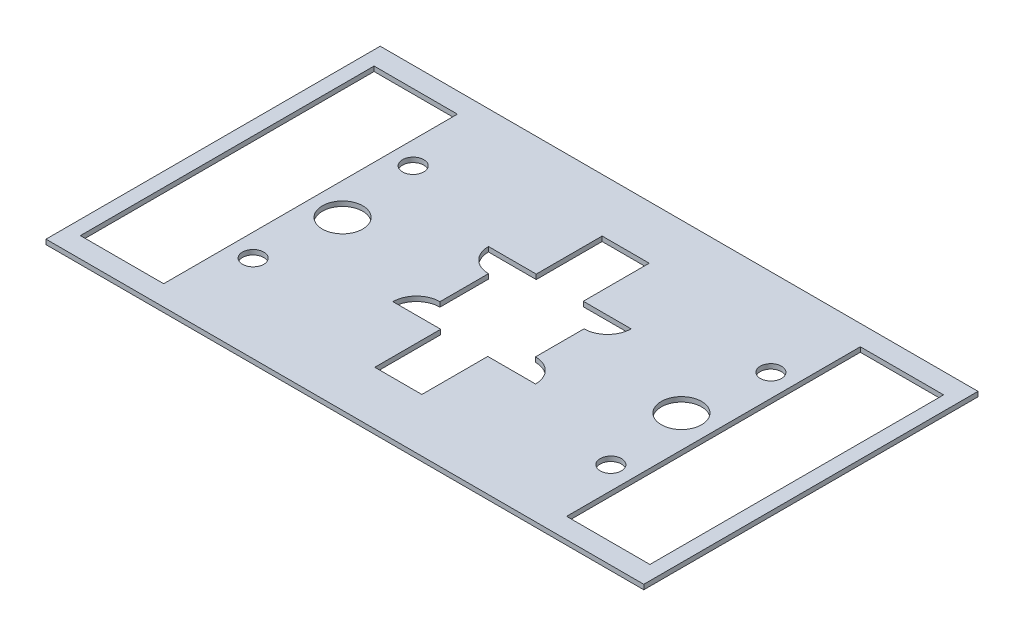
SolidWorks part; units mm, degrees
material "Copper"
ref_plane "Front Plane" through (0, 0, 0) normal (0, 0, 1) x (1, 0, 0)
ref_plane "Top Plane" through (0, 0, 0) normal (0, 1, 0) x (1, 0, 0)
ref_plane "Right Plane" through (0, 0, 0) normal (1, 0, 0) x (0, 0, -1)
sketch "Sketch1" plane through (0, 0, 0) normal (0, 1, 0) x (1, 0, 0)
  line L0 (-2.5, 5.075) -> (-2.5, 12.075)
  line L1 (-5, 5) -> (5, 5) construction
  line L2 (-5, 5) -> (-5, -5) construction
  line L3 (-5, -5) -> (5, -5) construction
  line L4 (5, 5) -> (5, -5) construction
  line L5 (-5.075, 5.075) -> (5.075, 5.075)
  line L6 (-5.075, 5.075) -> (-5.075, -5.075)
  line L7 (-5.075, -5.075) -> (5.075, -5.075)
  line L8 (5.075, 5.075) -> (5.075, -5.075)
  line L9 (-7.575, 7.575) -> (7.575, 7.575)
  line L10 (-7.575, 7.575) -> (-7.575, -7.575)
  line L11 (-7.575, -7.575) -> (7.575, -7.575)
  line L12 (7.575, 7.575) -> (7.575, -7.575)
  line L13 (-31.75, 17.75) -> (31.75, 17.75) construction
  line L14 (-31.75, 17.75) -> (-31.75, -17.75) construction
  line L15 (-31.75, -17.75) -> (31.75, -17.75) construction
  line L16 (31.75, 17.75) -> (31.75, -17.75) construction
  line L17 (-31.75, 17.75) -> (31.75, 17.75)
  line L18 (-31.75, 17.75) -> (-31.75, -17.75)
  line L19 (-31.75, -17.75) -> (31.75, -17.75)
  line L20 (31.75, 17.75) -> (31.75, -17.75)
  line L21 (-30.25, 15.6) -> (-21.4, 15.6)
  line L22 (-30.25, 15.6) -> (-30.25, -15.6)
  line L23 (-30.25, -15.6) -> (-21.4, -15.6)
  line L24 (-21.4, 15.6) -> (-21.4, -15.6)
  line L25 (21.4, 15.6) -> (30.25, 15.6)
  line L26 (21.4, 15.6) -> (21.4, -15.6)
  line L27 (21.4, -15.6) -> (30.25, -15.6)
  line L28 (30.25, 15.6) -> (30.25, -15.6)
  line L29 (-2.5, 12.075) -> (2.5, 12.075)
  line L30 (2.5, 12.075) -> (2.5, 5.075)
  line L31 (-2.5, -5.075) -> (-2.5, -12.075)
  line L32 (-2.5, -12.075) -> (2.5, -12.075)
  line L33 (2.5, -12.075) -> (2.5, -5.075)
  line L34 (-5.075, 5.075) -> (-5.075, 7.575)
  line L35 (5.075, 5.075) -> (5.075, 7.575)
  line L36 (5.075, -5.075) -> (5.075, -7.575)
  line L37 (-5.075, -5.075) -> (-5.075, -7.575)
  line L38 (-5.075, 5.075) -> (-7.575, 5.075)
  line L39 (5.075, 5.075) -> (7.575, 5.075)
  line L40 (-5.075, -5.075) -> (-7.575, -5.075)
  line L41 (5.075, -5.075) -> (7.575, -5.075)
  circle A0 centre (-5.075, 5.075) radius 2.5
  circle A1 centre (5.075, 5.075) radius 2.5
  circle A2 centre (5.075, -5.075) radius 2.5
  circle A3 centre (-5.075, -5.075) radius 2.5
  circle A4 centre (-19, 8.5) radius 1.13
  circle A5 centre (19, 8.5) radius 1.13
  circle A6 centre (19, -8.5) radius 1.13
  circle A7 centre (-19, -8.5) radius 1.13
  circle A8 centre (-18, 0) radius 2.1446
  circle A9 centre (18, 0) radius 2.1446
  point P4 (0, 5.075)
  point P13 (5.075, 0)
  point P14 (0, 5)
  point P16 (5, 0)
  point P25 (0, 17.75)
  point P26 (0, 7.575)
  point P31 (7.575, 0)
  point P32 (31.75, 0)
  point P37 (0, 17.75)
  point P38 (31.75, 0)
  point P47 (-30.25, 0)
  point P48 (-31.75, 0)
  point P63 (0, 12.075)
  point P72 (0, -12.075)
  point P75 (0, 0)
  dimension "D3" = 5
  dimension "D18" = 2.26
  dimension "D21" = 4.2892
  dimension "D1" = 10
  dimension "D2" = 10.15
  dimension "D4" = 35.5
  dimension "D5" = 63.5
  dimension "D6" = 63.5
  dimension "D7" = 35.5
  dimension "D8" = 2.15
  dimension "D10" = 31.2
  dimension "D11" = 8.85
  dimension "D12" = 2.15
  dimension "D15" = 8.5
  dimension "D19" = 18
  dimension "D20" = 18
  dimension "D22" = 5
  dimension "D23" = 7
  dimension "D24" = 7
  dimension "D13" = 1.5
  dimension "D9" = 1.5
  dimension "D14" = 12.75
  dimension "D16" = 8.5
  dimension "D17" = 12.75
extrude "Boss-Extrude1" add sketch "Sketch1" along normal blind 0.508 contours L20 L17 L18 L19 A9 A8 A7 A6 A5 A4 L9 L12 L11 L10 L21 L24 L23 L22 L25 L28 L27 L26 | A2 L11 L12 | A2 L12 A1 L8 | A1 L12 L9 | A0 L9 L10 | A3 L6 A0 L10 | A3 L10 L11 | A0 L5 L0 L9 | A1 L9 L30 L5 | A2 L7 L33 L11 | A3 L11 L31 L7 | L5 A0 L34 | L35 A1 L5 | L7 A2 L36 | L37 A3 L7 | L34 A0 L38 | L39 A1 L35 | L36 A2 L8 | L40 A3 L37
equation "\"D2@Sketch1\"=\"D1@Sketch1\"+0.15"
equation "\"D20@Sketch1\"=\"D19@Sketch1\""
equation "\"D24@Sketch1\"=\"D23@Sketch1\""
equation "\"D9@Sketch1\"=\"D13@Sketch1\""
equation "\"D16@Sketch1\"=\"D15@Sketch1\""
equation "\"D17@Sketch1\"=\"D14@Sketch1\""
